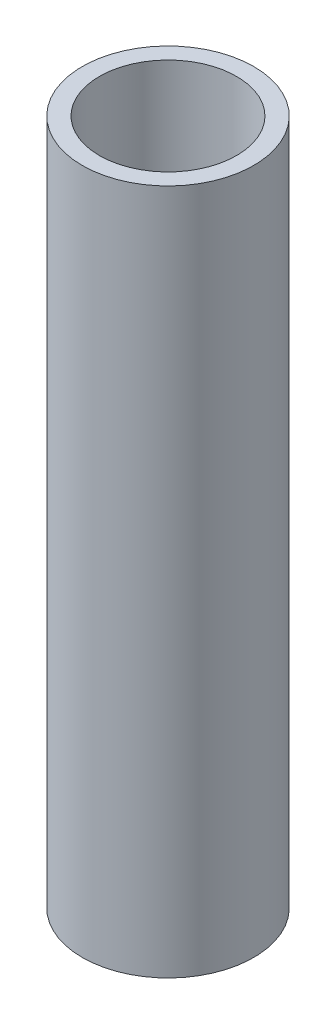
SolidWorks part; units mm, degrees
ref_plane "Front Plane" through (0, 0, 0) normal (0, 0, 1) x (1, 0, 0)
ref_plane "Top Plane" through (0, 0, 0) normal (0, 1, 0) x (1, 0, 0)
ref_plane "Right Plane" through (0, 0, 0) normal (1, 0, 0) x (0, 0, -1)
sketch "Sketch1" plane through (0, 0, 0) normal (0, 1, 0) x (1, 0, 0)
  circle A0 centre (0, 0) radius 12.5
  circle A1 centre (0, 0) radius 10
  dimension "D1" = 20
  dimension "D2" = 25
extrude "Boss-Extrude1" add sketch "Sketch1" along normal blind 100
